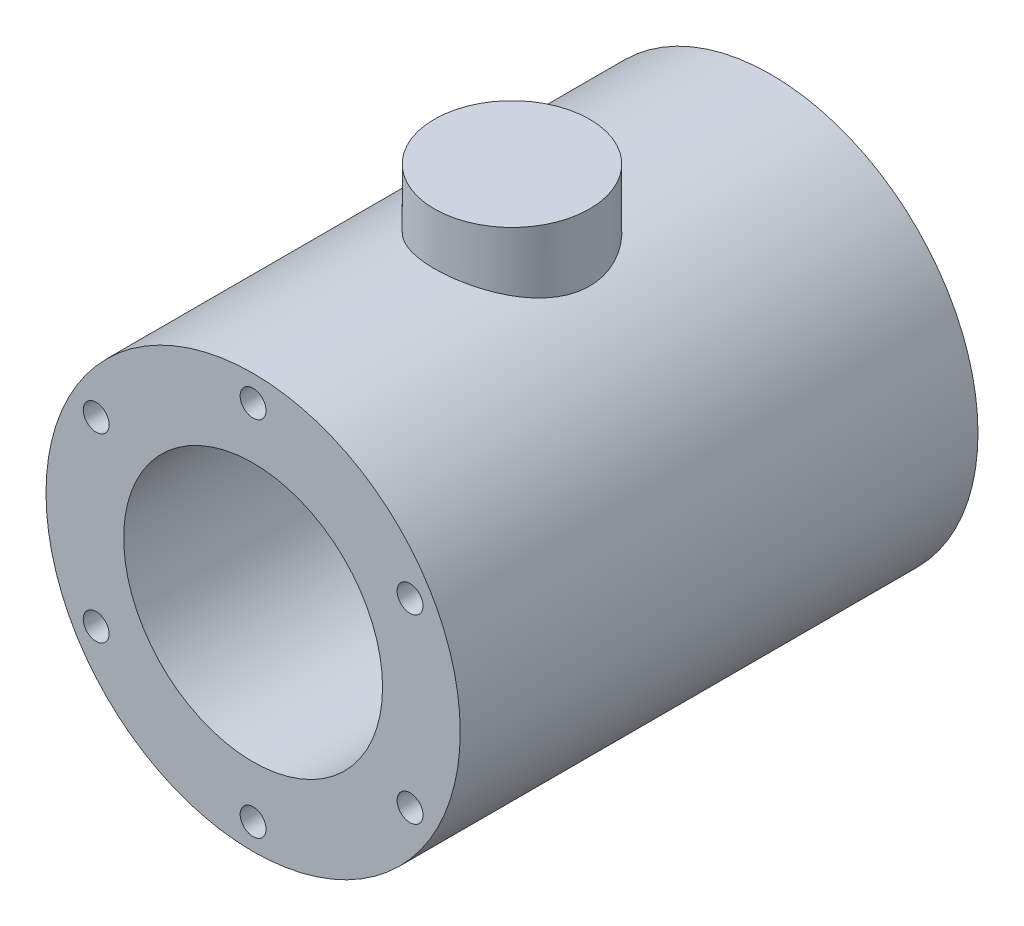
SolidWorks part; units mm, degrees
ref_plane "Front Plane" through (0, 0, 0) normal (0, 0, 1) x (1, 0, 0)
ref_plane "Top Plane" through (0, 0, 0) normal (0, 1, 0) x (1, 0, 0)
ref_plane "Right Plane" through (0, 0, 0) normal (1, 0, 0) x (0, 0, -1)
sketch "Sketch1" plane through (0, 0, 0) normal (0, 0, 1) x (1, 0, 0)
  circle A0 centre (0, 0) radius 40
  dimension "D1" = 80
extrude "body" add sketch "Sketch1" along normal blind 100 contours A0
sketch "Sketch3" plane through (0, 0, 0) normal (0, 0, 1) x (1, 0, 0)
  circle A0 centre (0, 0) radius 25
  dimension "D1" = 50
extrude "motor casing" cut sketch "Sketch3" along normal blind 246
sketch "Sketch4" plane through (0, 0, 0) normal (0, 0, 1) x (1, 0, 0)
  circle A2 centre (0, 0) radius 30
  circle A3 centre (0, 0) radius 30
  dimension "D1" = 5
extrude "slew bearing lip" cut sketch "Sketch4" along normal blind 7.5
sketch "Sketch6" plane through (0, 0, 0) normal (0, 1, 0) x (1, 0, 0)
  line L0 (-40, -50) -> (40, -50) construction
  line L1 (-40, 0) -> (-40, -100) construction
  line L2 (40, -100) -> (40, 0) construction
  circle A0 centre (0, -50) radius 15
  dimension "D1" = 30
extrude "base" add sketch "Sketch6" along normal blind 20 from offset 30
sketch "Sketch5" plane through (0, 0, 0) normal (0, 0, -1) x (-1, 0, 0)
  circle A0 centre (0, 35) radius 2.5
  circle A3 centre (0, 0) radius 35 construction
  circle A4 centre (30.3109, 17.5) radius 2.5
  circle A5 centre (30.3109, -17.5) radius 2.5
  circle A6 centre (0, -35) radius 2.5
  circle A7 centre (-30.3109, -17.5) radius 2.5
  circle A8 centre (-30.3109, 17.5) radius 2.5
  dimension "D1" = 5
  dimension "D2" = 70
  dimension "D3" = 6
extrude "screw holes" cut sketch "Sketch5" against normal through all
